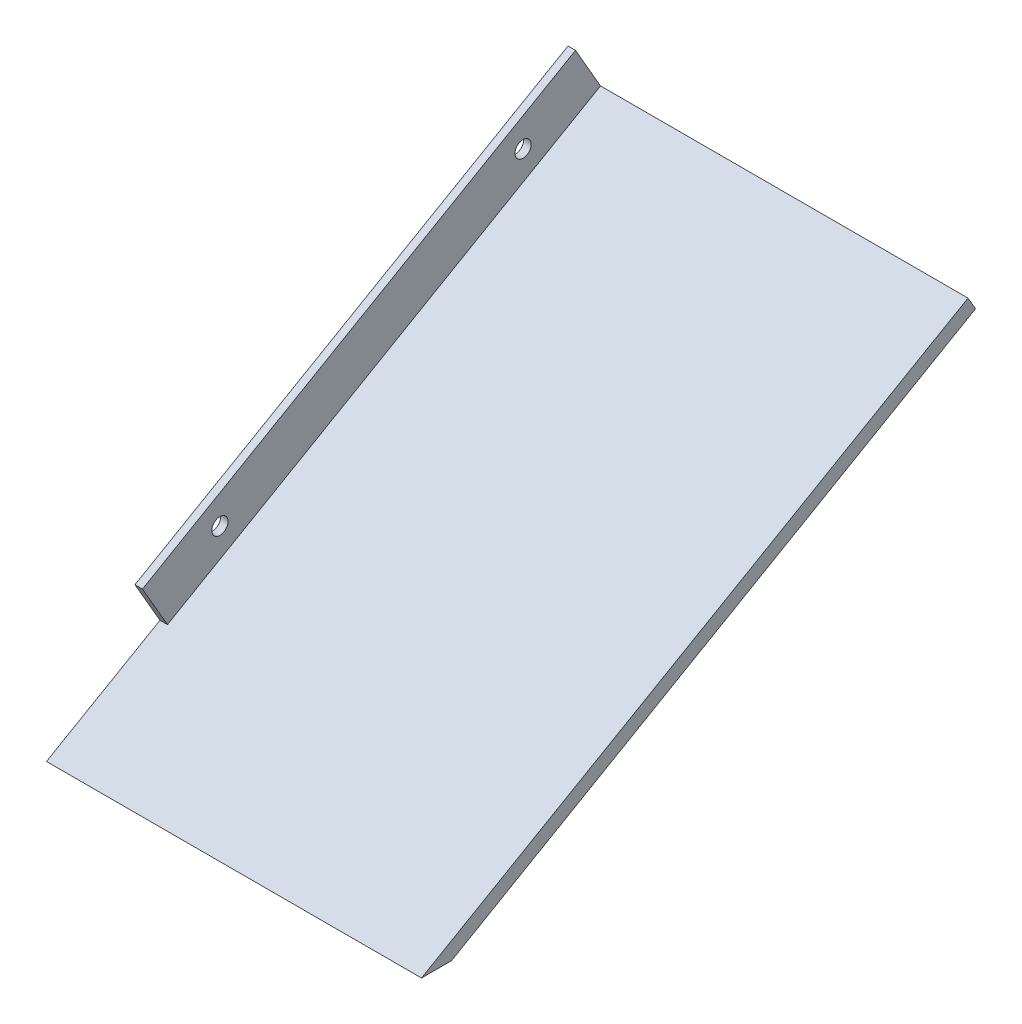
SolidWorks part; units mm, degrees
ref_plane "Front Plane" through (0, 0, 0) normal (0, 0, 1) x (1, 0, 0)
ref_plane "Top Plane" through (0, 0, 0) normal (0, 1, 0) x (1, 0, 0)
ref_plane "Right Plane" through (0, 0, 0) normal (1, 0, 0) x (0, 0, -1)
sketch "Sketch1" plane through (0, 0, 0) normal (1, 0, 0) x (0, 0, -1)
  line L0 (-71.8899, -27.3023) -> (-65.8899, -27.3023)
  line L1 (-65.8899, -27.3023) -> (38.9079, 33.2027)
  line L2 (-65.8899, -27.3023) -> (49934.1101, -27.3023) construction
  line L3 (38.9079, 33.2027) -> (37.4079, 35.8008)
  line L4 (-71.8899, -27.3023) -> (37.4079, 35.8008)
  dimension "D1" = 6
  dimension "D2" = 121.01
  dimension "D3" = 30
  dimension "D4" = 3
extrude "Boss-Extrude1" add sketch "Sketch1" along normal blind 75
sketch "Sketch2" plane through (0, 10.6525, 6.1502) normal (0, 0.866, 0.5) x (1, 0, 0)
  line L1 (0, 50.2965) -> (1.5, 50.2965)
  line L2 (0, 50.2965) -> (0, -49.7035)
  line L3 (0, -49.7035) -> (1.5, -49.7035)
  line L4 (1.5, 50.2965) -> (1.5, -49.7035)
  dimension "D1" = 1.5
  dimension "D2" = 100
extrude "Boss-Extrude2" add sketch "Sketch2" along normal blind 10
sketch "Sketch3" plane through (0, 0, 0) normal (-1, 0, 0) x (0, 0, 1)
  line L0 (-38.9079, 33.2027) -> (-32.4079, 44.461) construction
  line L4 (-32.4079, 44.461) -> (54.1947, -5.539) construction
  line L5 (54.1947, -5.539) -> (49.1947, -14.1992) construction
  circle A0 centre (-21.9175, 32.6309) radius 1.625
  circle A1 centre (38.7043, -2.3691) radius 1.625
  dimension "D1" = 3.25
  dimension "D2" = 15
  dimension "D3" = 5
  dimension "D4" = 3.25
  dimension "D5" = 15
  dimension "D6" = 5
extrude "Cut-Extrude1" cut sketch "Sketch3" against normal through all
